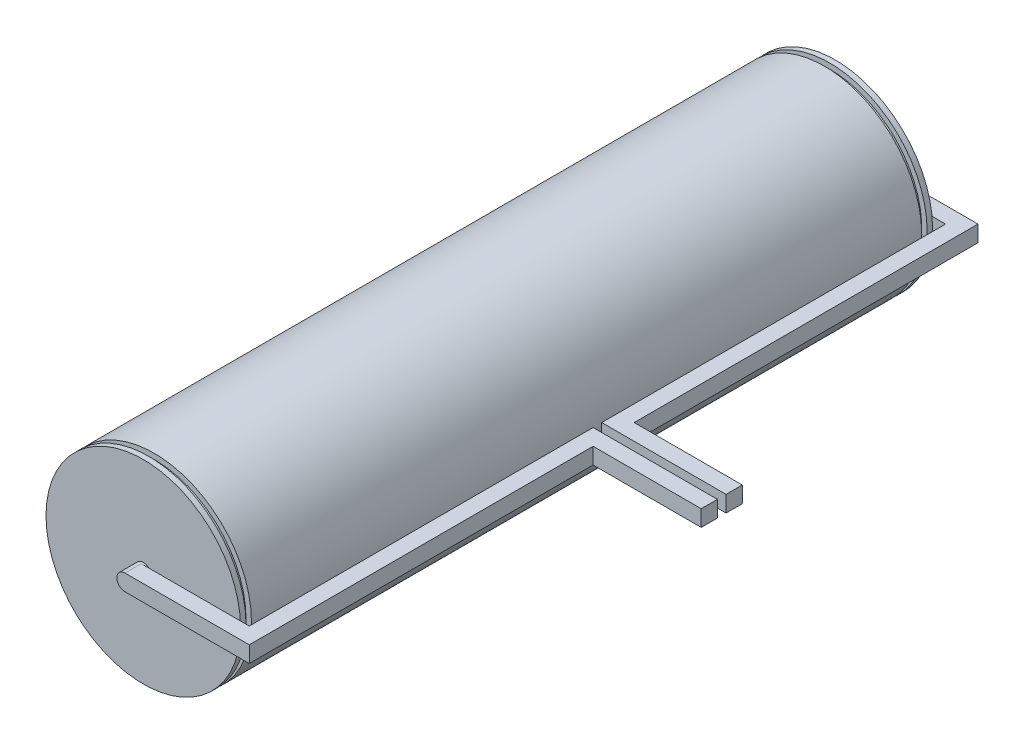
SolidWorks part; units mm, degrees
ref_plane "Plan de face" through (0, 0, 0) normal (0, 0, 1) x (1, 0, 0)
ref_plane "Plan de dessus" through (0, 0, 0) normal (0, 1, 0) x (1, 0, 0)
ref_plane "Plan de droite" through (0, 0, 0) normal (1, 0, 0) x (0, 0, -1)
sketch "Esquisse1" plane through (0, 0, 0) normal (0, 0, 1) x (1, 0, 0)
  circle A0 centre (0, 0) radius 9
  dimension "D1" = 18
extrude "Boss.-Extru.1" add sketch "Esquisse1" along normal blind 31
sketch "Esquisse3" plane through (0, 0, 0) normal (0, 0, -1) x (-1, 0, 0)
  circle A0 centre (0, 0) radius 8.5
  circle A1 centre (0, 0) radius 9 construction
  dimension "D1" = 0.5
extrude "Boss.-Extru.2" add sketch "Esquisse3" along normal blind 0.5
sketch "Esquisse4" plane through (0, 0, -0.5) normal (0, 0, -1) x (-1, 0, 0)
  circle A0 centre (0, 0) radius 9
extrude "Boss.-Extru.3" add sketch "Esquisse4" along normal blind 0.5
sketch "Esquisse5" plane through (0, 0, -1) normal (0, 0, -1) x (-1, 0, 0)
  circle A0 centre (0, 0) radius 0.75
  dimension "D1" = 1.5
extrude "Boss.-Extru.4" add sketch "Esquisse5" along normal blind 0.2
sketch "Esquisse6" plane through (0, 0, -1.2) normal (0, 0, -1) x (-1, 0, 0)
  line L1 (0, -0.75) -> (-11.5, -0.75)
  line L2 (0, -0.75) -> (0, 0.75)
  line L3 (0, 0.75) -> (-11.5, 0.75)
  line L4 (-11.5, -0.75) -> (-11.5, 0.75)
  circle A0 centre (0, 0) radius 0.75 construction
  circle A1 centre (0, 0) radius 0.75 construction
  circle A2 centre (0, 0) radius 0.75
  circle M2 centre (0, 0) radius 0.75
  dimension "D1" = 11.5
extrude "Boss.-Extru.5" add sketch "Esquisse6" along normal blind 1.5 contours L4 L1 L3 M2 | L2 M2 | L2 M2
sketch "Esquisse7" plane through (0, 0, -1.2) normal (0, 0, 1) x (1, 0, 0)
  line L0 (0, -0.75) -> (11.5, -0.75) construction
  line L1 (11.5, 0.75) -> (10, 0.75)
  line L2 (11.5, 0.75) -> (11.5, -0.75)
  line L3 (11.5, -0.75) -> (10, -0.75)
  line L4 (10, 0.75) -> (10, -0.75)
  dimension "D1" = 1.5
extrude "Boss.-Extru.6" add sketch "Esquisse7" along normal blind 31.8
sketch "Esquisse8" plane through (11.5, 0, 0) normal (1, 0, 0) x (0, 0, -1)
  line L0 (2.7, -0.75) -> (-30.6, -0.75) construction
  line L1 (-30.6, 0.75) -> (-29.1, 0.75)
  line L2 (-30.6, 0.75) -> (-30.6, -0.75)
  line L3 (-30.6, -0.75) -> (-29.1, -0.75)
  line L4 (-29.1, 0.75) -> (-29.1, -0.75)
  dimension "D1" = 1.5
extrude "Boss.-Extru.7" add sketch "Esquisse8" along normal blind 10
sketch "Esquisse10" plane through (0, 0, 31) normal (0, 0, 1) x (1, 0, 0)
  circle A0 centre (0, 0) radius 9
extrude "Boss.-Extru.8" add sketch "Esquisse10" along normal blind 31
sketch "Esquisse11" plane through (0, 0, 62) normal (0, 0, 1) x (1, 0, 0)
  circle A0 centre (0, 0) radius 8.5
  circle A1 centre (0, 0) radius 9 construction
  dimension "D1" = 0.5
extrude "Boss.-Extru.9" add sketch "Esquisse11" along normal blind 0.5
sketch "Esquisse12" plane through (0, 0, 62.5) normal (0, 0, 1) x (1, 0, 0)
  circle A0 centre (0, 0) radius 9
extrude "Boss.-Extru.10" add sketch "Esquisse12" along normal blind 0.5
sketch "Esquisse13" plane through (0, 0, 63) normal (0, 0, 1) x (1, 0, 0)
  circle A0 centre (0, 0) radius 0.75
  dimension "D1" = 1.5
extrude "Boss.-Extru.11" add sketch "Esquisse13" along normal blind 0.2
sketch "Esquisse15" plane through (0, 0, 63.2) normal (0, 0, 1) x (1, 0, 0)
  line L1 (0, -0.75) -> (11.5, -0.75)
  line L2 (0, -0.75) -> (0, 0.75)
  line L3 (0, 0.75) -> (11.5, 0.75)
  line L4 (11.5, -0.75) -> (11.5, 0.75)
  circle A0 centre (0, 0) radius 0.75 construction
  circle A1 centre (0, 0) radius 0.75
  circle M1 centre (0, 0) radius 0.75
  dimension "D1" = 11.5
extrude "Boss.-Extru.12" add sketch "Esquisse15" along normal blind 1.5 contours L1 L4 L3 M1 | L2 M1 | L2 M1
sketch "Esquisse16" plane through (0, 0, 63.2) normal (0, 0, -1) x (-1, 0, 0)
  line L0 (0, -0.75) -> (-11.5, -0.75) construction
  line L1 (-11.5, 0.75) -> (-10, 0.75)
  line L2 (-11.5, 0.75) -> (-11.5, -0.75)
  line L3 (-11.5, -0.75) -> (-10, -0.75)
  line L4 (-10, 0.75) -> (-10, -0.75)
  dimension "D1" = 1.5
extrude "Boss.-Extru.13" add sketch "Esquisse16" along normal blind 31.8
sketch "Esquisse17" plane through (11.5, 0, 0) normal (1, 0, 0) x (0, 0, -1)
  line L0 (-64.7, -0.75) -> (-31.4, -0.75) construction
  line L1 (-31.4, 0.75) -> (-32.9, 0.75)
  line L2 (-31.4, 0.75) -> (-31.4, -0.75)
  line L3 (-31.4, -0.75) -> (-32.9, -0.75)
  line L4 (-32.9, 0.75) -> (-32.9, -0.75)
  dimension "D1" = 1.5
extrude "Boss.-Extru.14" add sketch "Esquisse17" along normal blind 10
